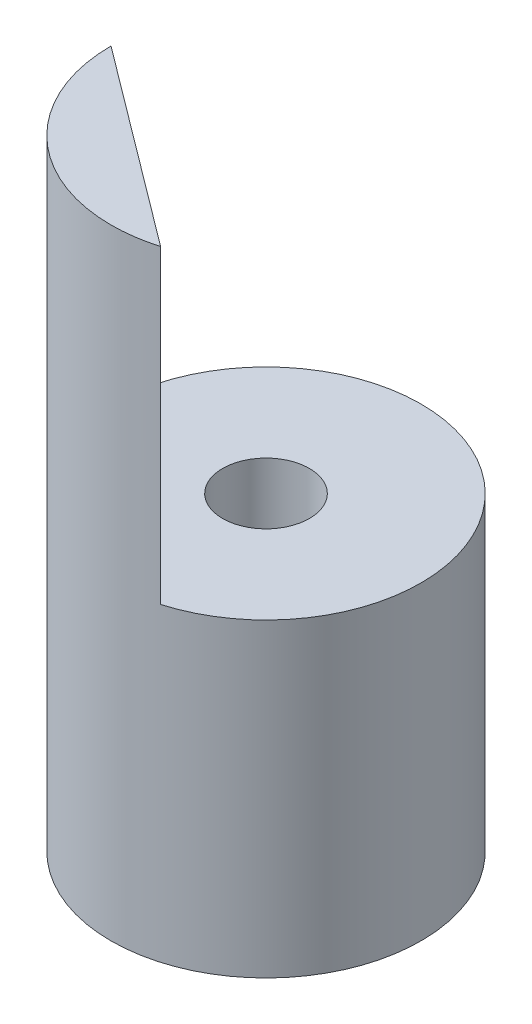
SolidWorks part; units mm, degrees
ref_plane "Alzado" through (0, 0, 0) normal (0, 0, 1) x (1, 0, 0)
ref_plane "Planta" through (0, 0, 0) normal (0, 1, 0) x (1, 0, 0)
ref_plane "Vista lateral" through (0, 0, 0) normal (1, 0, 0) x (0, 0, -1)
sketch "Croquis1" plane through (0, 0, 0) normal (0, 1, 0) x (1, 0, 0)
  circle A0 centre (0, 0) radius 7.5
  point P1 (0, 0)
  dimension "D1" = 15
extrude "Saliente-Extruir1" add sketch "Croquis1" against normal mid plane 15
sketch "Croquis2" plane through (0, 7.5, 0) normal (0, 1, 0) x (1, 0, 0)
  line L0 (2.1, -7.2) -> (-7.5, 0)
  arc A0 (2.1, -7.2) -> (-7.5, 0) centre (0, 0) cw
  circle A1 centre (0, 0) radius 7.5 construction
  dimension "D2" = 4.5
  dimension "D1" = 12
other "Alinear grupo1"
extrude "Saliente-Extruir2" add sketch "Croquis2" along normal blind 15
sketch "Croquis3" plane through (0, 7.5, 0) normal (0, 1, 0) x (1, 0, 0)
  circle A0 centre (0, 0) radius 2.1
  dimension "D1" = 4.2
extrude "Cortar-Extruir2" cut sketch "Croquis3" against normal through all contours A0
